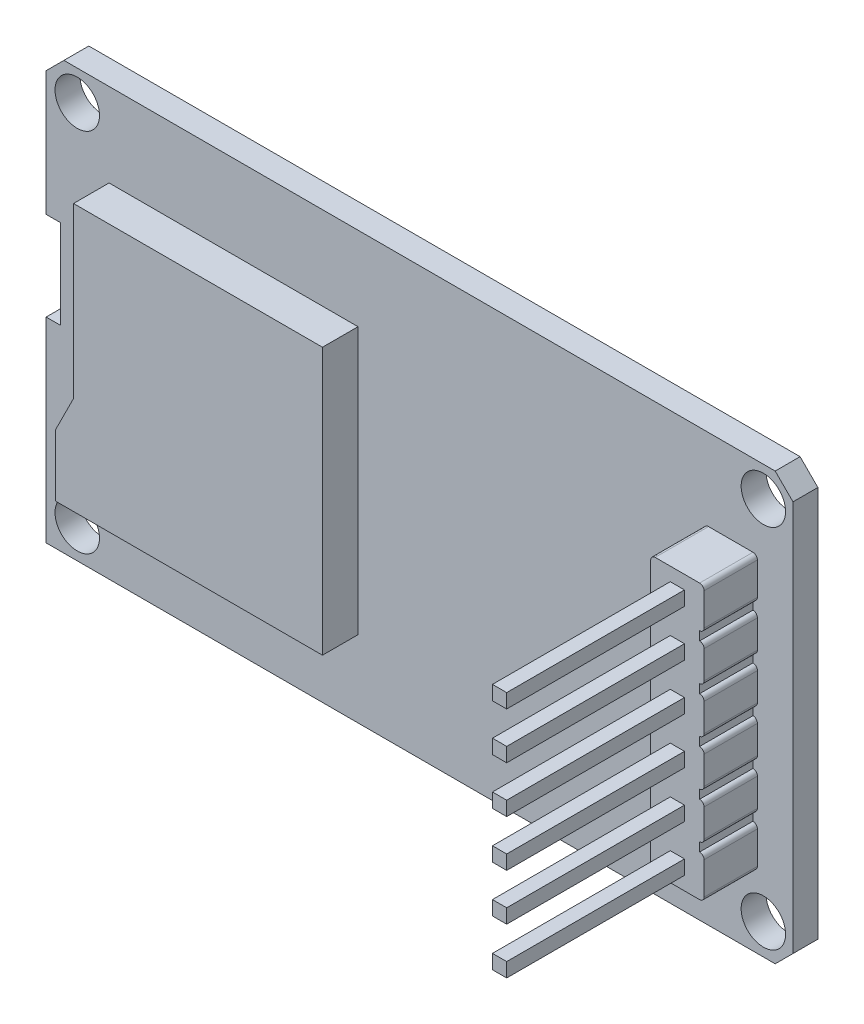
SolidWorks part; units mm, degrees
ref_plane "Front Plane" through (0, 0, 0) normal (0, 0, 1) x (1, 0, 0)
ref_plane "Top Plane" through (0, 0, 0) normal (0, 1, 0) x (1, 0, 0)
ref_plane "Right Plane" through (0, 0, 0) normal (1, 0, 0) x (0, 0, -1)
sketch "Sketch1" plane through (0, 0, 0) normal (0, 0, 1) x (1, 0, 0)
  line L0 (-17.6235, 12) -> (-16.6235, 13)
  line L1 (-17.6235, -11) -> (23.3765, -11)
  line L3 (-16.6235, 13) -> (23.3765, 13)
  line L4 (24.3765, -10) -> (24.3765, 12)
  line L5 (23.3765, 13) -> (24.3765, 12)
  line L6 (23.3765, -11) -> (24.3765, -10)
  line L7 (-17.6235, 0) -> (-16.8235, 0)
  line L8 (-16.8235, 0) -> (-16.8235, 5)
  line L9 (-16.8235, 5) -> (-17.6235, 5)
  line L10 (-17.6235, 5) -> (-17.6235, 12)
  line L11 (-17.6235, 0) -> (-17.6235, -11)
  point P1 (24.3765, 13)
  point P2 (-17.6235, 13)
  point P3 (24.3765, -11)
  dimension "D1" = 42
  dimension "D2" = 24
  dimension "D3" = 11
  dimension "D4" = 5
  dimension "D8" = 0.8
extrude "Boss-Extrude1" add sketch "Sketch1" along normal blind 1.4 contours L0 L3 L5 L4 L6 L1 L11 L7 L8 L9 L10
hole_wizard "Ø2.5 (2.5) Diameter Slot1" positions "Sketch4" profile "Sketch5" size "Ø2.5" standard "ISO" slot yes end condition through all
sketch "Sketch4" plane through (0, 0, 1.4) normal (0, 0, 1) x (1, 0, 0)
  point P0 (-15.8743, -9.2692)
  point P2 (-15.8743, 11.3127)
  point P4 (22.7108, -9.2692)
  point P6 (22.7108, 11.3127)
sketch "Sketch5" plane through (-15.8743, -9.2692, 1.4) normal (1, 0, 0) x (0, -1, 0)
  line L0 (0, 0) -> (0, 1.4)
  line L1 (0, 1.4) -> (1.25, 1.4)
  line L2 (1.25, 1.4) -> (1.25, 0)
  line L5 (1.25, 0) -> (0, 0)
  line L11 (0, -6.35) -> (0, 15.6736) construction
  dimension "Thru Hole Dia." = 2.5
  dimension "Thru Hole Depth" = 1.4
sketch "Sketch6" plane through (0, 0, 1.4) normal (0, 0, 1) x (1, 0, 0)
  line L0 (-15.0835, -6.7) -> (-0.0835, -6.7)
  line L1 (-17.6235, -11) -> (23.3765, -11) construction
  line L2 (-17.6235, 0) -> (-17.6235, -11) construction
  line L3 (-0.0835, -6.7) -> (-0.0835, 8.3)
  line L4 (-0.0835, 8.3) -> (-14.0835, 8.3)
  line L5 (-14.0835, 8.3) -> (-14.0835, -1.2)
  line L6 (-14.0835, -1.2) -> (-15.0835, -3.2)
  line L7 (-15.0835, -3.2) -> (-15.0835, -6.7)
  dimension "D1" = 4.3
  dimension "D2" = 15
  dimension "D3" = 2.54
  dimension "D4" = 15
  dimension "D5" = 14
  dimension "D6" = 3.5
  dimension "D7" = 9.5
extrude "Boss-Extrude2" add sketch "Sketch6" along normal blind 2
sketch "Sketch7" plane through (0, 0, 1.4) normal (0, 0, 1) x (1, 0, 0)
  line L0 (22.1265, 6.1) -> (22.1265, 5.6)
  line L1 (22.1265, 8.42) -> (19.6265, 8.42)
  line L2 (19.6265, 6.1) -> (19.6265, 5.6)
  line L3 (22.1265, -7) -> (19.6265, -7)
  line L4 (19.6265, 3.53) -> (19.6265, 3.03)
  line L5 (-17.6235, -11) -> (23.3765, -11) construction
  line L6 (22.3765, 8.17) -> (22.3765, 6.35)
  line L7 (19.3765, 8.17) -> (19.3765, 6.35)
  line L8 (19.3765, 5.35) -> (19.3765, 3.78)
  line L9 (22.3765, 5.35) -> (22.3765, 3.78)
  line L10 (22.3765, 2.78) -> (22.3765, 1.21)
  line L11 (22.1265, -1.61) -> (22.1265, -2.11)
  line L12 (19.6265, -1.61) -> (19.6265, -2.11)
  line L13 (22.1265, -4.18) -> (22.1265, -4.68)
  line L14 (19.6265, -4.68) -> (19.6265, -4.18)
  line L21 (19.3765, 2.78) -> (19.3765, 1.21)
  line L22 (19.3765, 0.21) -> (19.3765, -1.36)
  line L23 (22.3765, 0.21) -> (22.3765, -1.36)
  line L24 (22.3765, -2.36) -> (22.3765, -3.93)
  line L25 (19.3765, -2.36) -> (19.3765, -3.93)
  line L26 (19.3765, -4.93) -> (19.3765, -6.75)
  line L27 (22.3765, -4.93) -> (22.3765, -6.75)
  line L28 (22.1265, 3.53) -> (22.1265, 3.03)
  line L29 (22.1265, 0.96) -> (22.1265, 0.46)
  line L30 (19.6265, 0.96) -> (19.6265, 0.46)
  arc A0 (22.3765, -6.75) -> (22.1265, -7) centre (22.1265, -6.75) cw
  arc A1 (19.6265, -7) -> (19.3765, -6.75) centre (19.6265, -6.75) cw
  arc A2 (19.6265, -4.68) -> (19.3765, -4.93) centre (19.6265, -4.93) ccw
  arc A3 (22.1265, -4.68) -> (22.3765, -4.93) centre (22.1265, -4.93) cw
  arc A4 (19.6265, -4.18) -> (19.3765, -3.93) centre (19.6265, -3.93) cw
  arc A5 (22.1265, -4.18) -> (22.3765, -3.93) centre (22.1265, -3.93) ccw
  arc A6 (22.1265, -2.11) -> (22.3765, -2.36) centre (22.1265, -2.36) cw
  arc A7 (19.6265, -2.11) -> (19.3765, -2.36) centre (19.6265, -2.36) ccw
  arc A8 (19.6265, -1.61) -> (19.3765, -1.36) centre (19.6265, -1.36) cw
  arc A9 (22.1265, -1.61) -> (22.3765, -1.36) centre (22.1265, -1.36) ccw
  arc A10 (22.1265, 0.46) -> (22.3765, 0.21) centre (22.1265, 0.21) cw
  arc A11 (19.6265, 0.46) -> (19.3765, 0.21) centre (19.6265, 0.21) ccw
  arc A12 (19.6265, 0.96) -> (19.3765, 1.21) centre (19.6265, 1.21) cw
  arc A13 (22.1265, 0.96) -> (22.3765, 1.21) centre (22.1265, 1.21) ccw
  arc A14 (19.6265, 3.03) -> (19.3765, 2.78) centre (19.6265, 2.78) ccw
  arc A15 (22.1265, 3.03) -> (22.3765, 2.78) centre (22.1265, 2.78) cw
  arc A16 (22.1265, 3.53) -> (22.3765, 3.78) centre (22.1265, 3.78) ccw
  arc A17 (19.6265, 3.53) -> (19.3765, 3.78) centre (19.6265, 3.78) cw
  arc A18 (19.3765, 5.35) -> (19.6265, 5.6) centre (19.6265, 5.35) cw
  arc A19 (22.1265, 5.6) -> (22.3765, 5.35) centre (22.1265, 5.35) cw
  arc A20 (22.1265, 6.1) -> (22.3765, 6.35) centre (22.1265, 6.35) ccw
  arc A21 (19.6265, 6.1) -> (19.3765, 6.35) centre (19.6265, 6.35) cw
  arc A22 (19.6265, 8.42) -> (19.3765, 8.17) centre (19.6265, 8.17) ccw
  arc A23 (22.1265, 8.42) -> (22.3765, 8.17) centre (22.1265, 8.17) cw
  point P11 (19.3765, -7)
  point P73 (19.3765, 8.42)
  point P76 (22.3765, 8.42)
  dimension "D1" = 0.25
  dimension "D2" = 3
  dimension "D3" = 15.42
  dimension "D4" = 4
extrude "Boss-Extrude3" add sketch "Sketch7" along normal blind 3
sketch "Sketch8" plane through (0, 0, 4.4) normal (0, 0, 1) x (1, 0, 0)
  line L1 (20.4765, -5.44) -> (21.2765, -5.44)
  line L2 (20.4765, -5.44) -> (20.4765, -6.24)
  line L3 (20.4765, -6.24) -> (21.2765, -6.24)
  line L4 (21.2765, -5.44) -> (21.2765, -6.24)
  line L5 (20.4765, -5.44) -> (21.2765, -6.24) construction
  line L6 (20.4765, -6.24) -> (21.2765, -5.44) construction
  line L8 (21.2765, -2.82) -> (21.2765, -3.62)
  line L9 (20.4765, -2.82) -> (21.2765, -2.82)
  line L10 (20.4765, -2.82) -> (20.4765, -3.62)
  line L11 (20.4765, -3.62) -> (21.2765, -3.62)
  line L12 (21.2765, -0.2) -> (21.2765, -1)
  line L13 (20.4765, -0.2) -> (21.2765, -0.2)
  line L14 (20.4765, -0.2) -> (20.4765, -1)
  line L15 (20.4765, -1) -> (21.2765, -1)
  line L16 (21.2765, 2.42) -> (21.2765, 1.62)
  line L17 (20.4765, 2.42) -> (21.2765, 2.42)
  line L18 (20.4765, 2.42) -> (20.4765, 1.62)
  line L19 (20.4765, 1.62) -> (21.2765, 1.62)
  line L20 (21.2765, 5.04) -> (21.2765, 4.24)
  line L21 (20.4765, 5.04) -> (21.2765, 5.04)
  line L22 (20.4765, 5.04) -> (20.4765, 4.24)
  line L23 (20.4765, 4.24) -> (21.2765, 4.24)
  line L24 (21.2765, 7.66) -> (21.2765, 6.86)
  line L25 (20.4765, 7.66) -> (21.2765, 7.66)
  line L26 (20.4765, 7.66) -> (20.4765, 6.86)
  line L27 (20.4765, 6.86) -> (21.2765, 6.86)
  point P0 (20.8765, -5.84)
  dimension "D1" = 0.8
  dimension "D2" = 0.8
  dimension "D3" = 6
extrude "Boss-Extrude4" add sketch "Sketch8" along normal blind 10
